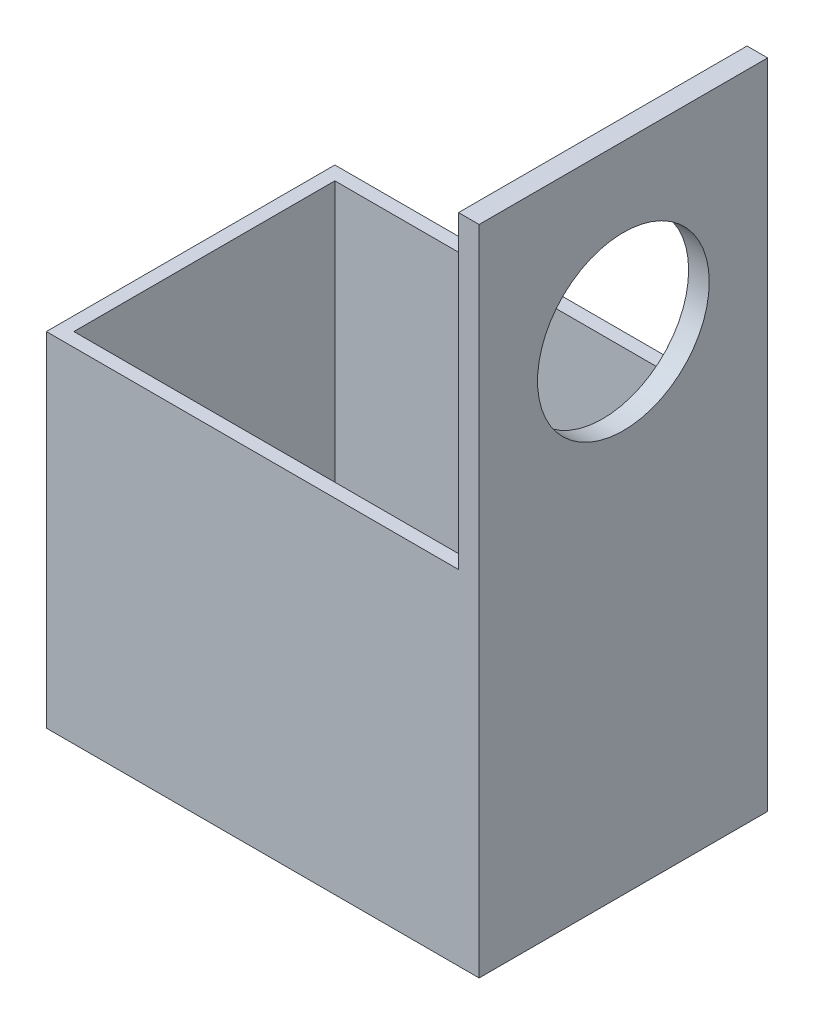
SolidWorks part; units mm, degrees
ref_plane "Front Plane" through (0, 0, 0) normal (0, 0, 1) x (1, 0, 0)
ref_plane "Top Plane" through (0, 0, 0) normal (0, 1, 0) x (1, 0, 0)
ref_plane "Right Plane" through (0, 0, 0) normal (1, 0, 0) x (0, 0, -1)
sketch "Sketch1" plane through (0, 0, 0) normal (0, 1, 0) x (1, 0, 0)
  line L1 (-30, -21) -> (30, -21)
  line L2 (-30, -21) -> (-30, 21)
  line L3 (-30, 21) -> (30, 21)
  line L4 (30, -21) -> (30, 21)
  line L5 (-30, -21) -> (30, 21) construction
  line L6 (-30, 21) -> (30, -21) construction
  line L7 (-28, -19) -> (28, -19)
  line L8 (-28, -19) -> (-28, 19)
  line L9 (-28, 19) -> (28, 19)
  line L10 (28, -19) -> (28, 19)
  line L11 (-28, -19) -> (28, 19) construction
  line L12 (-28, 19) -> (28, -19) construction
  point P0 (0, 0)
  point P6 (0, 0)
  dimension "D1" = 60
  dimension "D2" = 42
  dimension "D3" = 2
  dimension "D5" = 2
extrude "Boss-Extrude1" add sketch "Sketch1" along normal blind 50
sketch "Sketch2" plane through (30, 0, 0) normal (1, 0, 0) x (0, 0, -1)
  line L1 (-21, 0) -> (21, 0)
  line L2 (-21, 0) -> (-21, 95)
  line L3 (-21, 95) -> (21, 95)
  line L4 (21, 0) -> (21, 95)
  dimension "D1" = 95
extrude "Boss-Extrude2" add sketch "Sketch2" along normal blind 3 contours L3 L4 L1 L2
sketch "Sketch3" plane through (33, 0, 0) normal (1, 0, 0) x (0, 0, -1)
  line L0 (-21, 95) -> (21, 95) construction
  circle A0 centre (0, 71) radius 12.5
  dimension "D1" = 25
  dimension "D2" = 24
extrude "Cut-Extrude1" cut sketch "Sketch3" against normal blind 3
